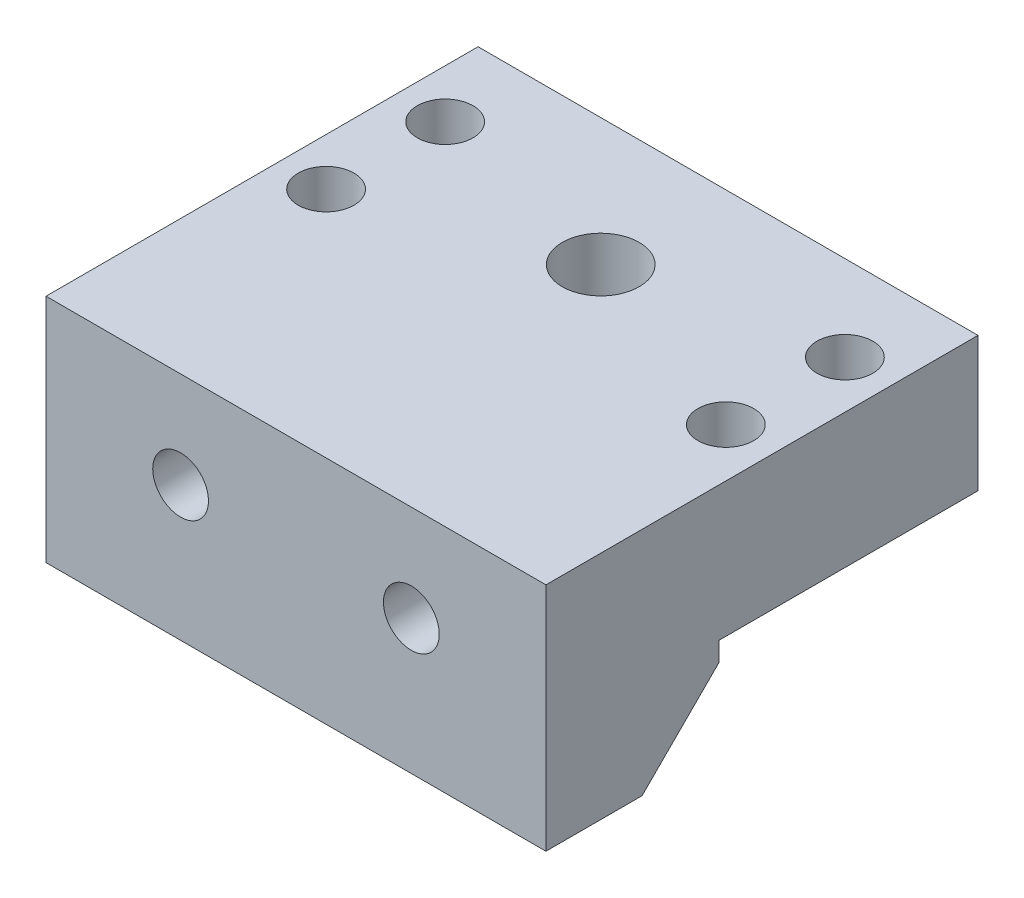
SolidWorks part; units mm, degrees
ref_plane "Front Plane" through (0, 0, 0) normal (0, 0, 1) x (1, 0, 0)
ref_plane "Top Plane" through (0, 0, 0) normal (0, 1, 0) x (1, 0, 0)
ref_plane "Right Plane" through (0, 0, 0) normal (1, 0, 0) x (0, 0, -1)
sketch "Sketch1" plane through (0, 0, 0) normal (0, 1, 0) x (1, 0, 0)
  line L0 (16, 13.7) -> (16, 0) construction
  line L1 (0, 0) -> (32, 0)
  line L2 (0, 0) -> (0, 26.9419)
  line L3 (0, 26.9419) -> (32, 26.9419)
  line L4 (32, 0) -> (32, 26.9419)
  circle A0 centre (16, 13.7) radius 4
  dimension "D2" = 13.7
  dimension "D3" = 8
  dimension "D1" = 32
extrude "Boss-Extrude1" add sketch "Sketch1" along normal blind 10
sketch "Sketch2" plane through (0, 10, 0) normal (0, 1, 0) x (1, 0, 0)
  line L0 (16, 13.7) -> (16, 22.5709) construction
  line L1 (0, 26.9419) -> (-10, 26.9419)
  line L2 (0, 26.9419) -> (0, 0)
  line L3 (0, 0) -> (-10, 0)
  line L4 (-10, 26.9419) -> (-10, 0)
  line L5 (32, 0) -> (42, 0)
  line L6 (42, 26.9419) -> (42, 0)
  line L7 (32, 26.9419) -> (42, 26.9419)
  line L8 (32, 26.9419) -> (32, 0)
  line L9 (0, 0) -> (32, 0) construction
  dimension "D1" = 10
extrude "Boss-Extrude2" add sketch "Sketch2" against normal blind 8
sketch "Sketch3" plane through (-10, 0, 0) normal (-1, 0, 0) x (0, 0, 1)
  line L1 (0, 0) -> (8, -8)
  line L2 (8, -8) -> (18, -8)
  line L3 (-26.9419, 0) -> (0, 0) construction
  line L4 (-26.9419, 10) -> (0, 10) construction
  line L5 (0, 0) -> (0, 10)
  line L6 (18, -8) -> (18, 10)
  line L7 (18, 10) -> (0, 10)
  dimension "D1" = 135
  dimension "D2" = 18
extrude "Boss-Extrude3" add sketch "Sketch3" against normal up to surface (52 mm away) up to face at (42, 6, -13.471)
sketch "Sketch4" plane through (0, 0, -26.9419) normal (0, 0, -1) x (-1, 0, 0)
  line L2 (-28, 6) -> (-4, 6) construction
  line L4 (-28, 6) -> (-42, 6) construction
  line L5 (-42, 2) -> (-42, 10) construction
  line L7 (10, 2) -> (10, 10) construction
  point P0 (-28, 6)
  point P2 (-4, 6)
  dimension "D1" = 14
  dimension "D2" = 14
hole_wizard "M5 Clearance Hole1" positions "Sketch4" profile "Sketch5" hole size "M5" standard "ISO" end condition through all
sketch "Sketch5" plane through (28, 6, -26.9419) normal (1, 0, 0) x (0, 1, 0)
  line L0 (0, 0) -> (0, 44.9419)
  line L1 (0, 44.9419) -> (2.9, 44.9419)
  line L2 (2.9, 44.9419) -> (2.9, 0)
  line L5 (2.9, 0) -> (0, 0)
  line L11 (0, -6.35) -> (0, 107.95) construction
  dimension "Thru Hole Dia." = 5.8
  dimension "Thru Hole Depth" = 44.9419
sketch "Sketch6" plane through (0, 10, 0) normal (0, 1, 0) x (1, 0, 0)
  line L4 (42, 26.9419) -> (-10, 26.9419)
  line L5 (-10, 26.9419) -> (-10, -18)
  line L6 (-10, -18) -> (42, -18)
  line L7 (42, -18) -> (42, 26.9419)
  line L8 (42, 26.9419) -> (-10, 26.9419)
  line L9 (-10, 26.9419) -> (-10, -18)
  line L10 (-10, -18) -> (42, -18)
  line L11 (42, -18) -> (42, 26.9419)
  circle A1 centre (16, 13.7) radius 4
  circle A2 centre (16, 13.7) radius 4
  dimension "D1" = 0
  dimension "D2" = 0
extrude "Boss-Extrude4" add sketch "Sketch6" along normal blind 6
sketch "Sketch7" plane through (0, 16, 0) normal (0, 1, 0) x (1, 0, 0)
  point P0 (37.0446, 18.0514)
  point P3 (36.9219, 5.7904)
  point P6 (-4.9533, 18.4714)
  point P9 (-5.076, 6.2104)
hole_wizard "M5 Clearance Hole2" positions "Sketch7" profile "Sketch8" hole size "M5" standard "ISO" end condition through all
sketch "Sketch8" plane through (37.0446, 16, -18.0514) normal (1, 0, 0) x (0, 0, 1)
  line L0 (0, 0) -> (0, 24)
  line L1 (0, 24) -> (2.9, 24)
  line L2 (2.9, 24) -> (2.9, 0)
  line L5 (2.9, 0) -> (0, 0)
  line L11 (0, -6.35) -> (0, 107.95) construction
  dimension "Thru Hole Dia." = 5.8
  dimension "Thru Hole Depth" = 24
